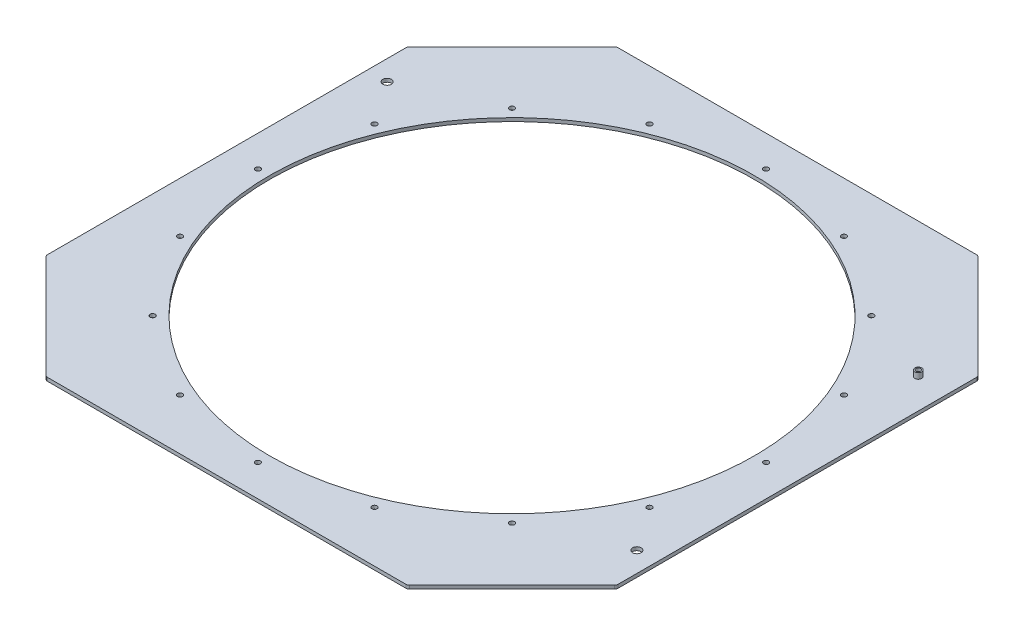
SolidWorks part; units mm, degrees
material "ASTM A36 Steel"
ref_plane "Front Plane" through (0, 0, 0) normal (0, 0, 1) x (1, 0, 0)
ref_plane "Top Plane" through (0, 0, 0) normal (0, 1, 0) x (1, 0, 0)
ref_plane "Right Plane" through (0, 0, 0) normal (1, 0, 0) x (0, 0, -1)
sketch "Sketch1" plane through (0, 0, 0) normal (0, 1, 0) x (1, 0, 0)
  line L5 (-243.4315, -243.4315) -> (243.4315, 243.4315) construction
  line L6 (-300, 300) -> (243.4315, -243.4315) construction
  line L18 (315.0665, 496.5) -> (497.5, 314.0665)
  line L19 (-314.0665, -497.5) -> (315.0665, -497.5)
  line L20 (-496.5, -315.0665) -> (-496.5, 314.0665)
  line L21 (-314.0665, 496.5) -> (315.0665, 496.5)
  line L22 (497.5, -315.0665) -> (497.5, 314.0665)
  line L23 (-405.7832, -405.7832) -> (405.7832, 405.7832) construction
  line L24 (-405.2832, 405.2832) -> (406.2832, -406.2832) construction
  line L25 (497.5, -315.0665) -> (315.0665, -497.5)
  line L30 (406.2832, -406.2832) -> (-405.2832, 405.2832) construction
  line L31 (498.06, 498.06) -> (-405.7832, -405.7832) construction
  line L32 (-496.5, -315.0665) -> (-314.0665, -497.5)
  line L33 (-314.0665, 496.5) -> (-496.5, 314.0665)
  point P0 (0, 0)
  point P7 (0, 0)
  point P10 (0, 0)
  point P17 (0, 0)
  dimension "D1" = 258
  dimension "D2" = 135
  dimension "D3" = 258
  dimension "D4" = 994
  dimension "D5" = 258
  dimension "D6" = 258
  dimension "D7" = 135
  dimension "D8" = 135
  dimension "D9" = 994
  dimension "D10" = 496.5
  dimension "D11" = 497.5
extrude "Boss-Extrude1" add sketch "Sketch1" along normal blind 6
sketch "Sketch2" plane through (0, 6, 0) normal (0, 1, 0) x (1, 0, 0)
  circle A0 centre (0, 0) radius 422.5
  dimension "D1" = 845
extrude "Cut-Extrude1" cut sketch "Sketch2" against normal blind 6
sketch "Sketch3" plane through (0, 6, 0) normal (0, 1, 0) x (1, 0, 0)
  circle A0 centre (0, 0) radius 442.5 construction
  circle A1 centre (0, 442.5) radius 4.5
  dimension "D1" = 885
  dimension "D2" = 9
extrude "Cut-Extrude2" cut sketch "Sketch3" against normal blind 6
pattern_circular "CirPattern1" count 16 every 22.5 about axis through (0, 0, 0) along (0, 1, 0) of "Cut-Extrude2"
sketch "Sketch4" plane through (0, 6, 0) normal (0, 1, 0) x (1, 0, 0)
  line L1 (497.5, -315.0665) -> (497.5, 314.0665) construction
  circle A0 centre (445.5, 262.0665) radius 3
  dimension "D3" = 6
  dimension "D1" = 52
  dimension "D2" = 52
extrude "Cut-Extrude3" cut sketch "Sketch4" against normal blind 10
sketch "Sketch5" plane through (0, 6, 0) normal (0, 1, 0) x (1, 0, 0)
  line L0 (-496.5, 314.0665) -> (-496.5, -315.0665) construction
  line L1 (497.5, -315.0665) -> (497.5, 314.0665) construction
  circle A0 centre (-461.5, 244.0665) radius 7.5
  circle A1 centre (462.5, -245.0665) radius 7.5
  dimension "D3" = 70
  dimension "D5" = 15
  dimension "D6" = 15
  dimension "D1" = 35
  dimension "D2" = 70
  dimension "D4" = 35
extrude "Cut-Extrude4" cut sketch "Sketch5" against normal blind 10
fillet "Fillet1" radius 6 8 edges at (497.5, 3, -314.0665) (315.0665, 3, -496.5) (-314.0665, 3, -496.5) (-496.5, 3, -314.0665) (-496.5, 3, 315.0665) (-314.0665, 3, 497.5) (315.0665, 3, 497.5) (497.5, 3, 315.0665)
sketch "Sketch6" plane through (0, 6, 0) normal (0, 1, 0) x (1, 0, 0)
  circle A0 centre (445.5, 262.0665) radius 4
  dimension "D1" = 8
extrude "Extrude-Thin1" add sketch "Sketch6" along normal blind 10 thin
